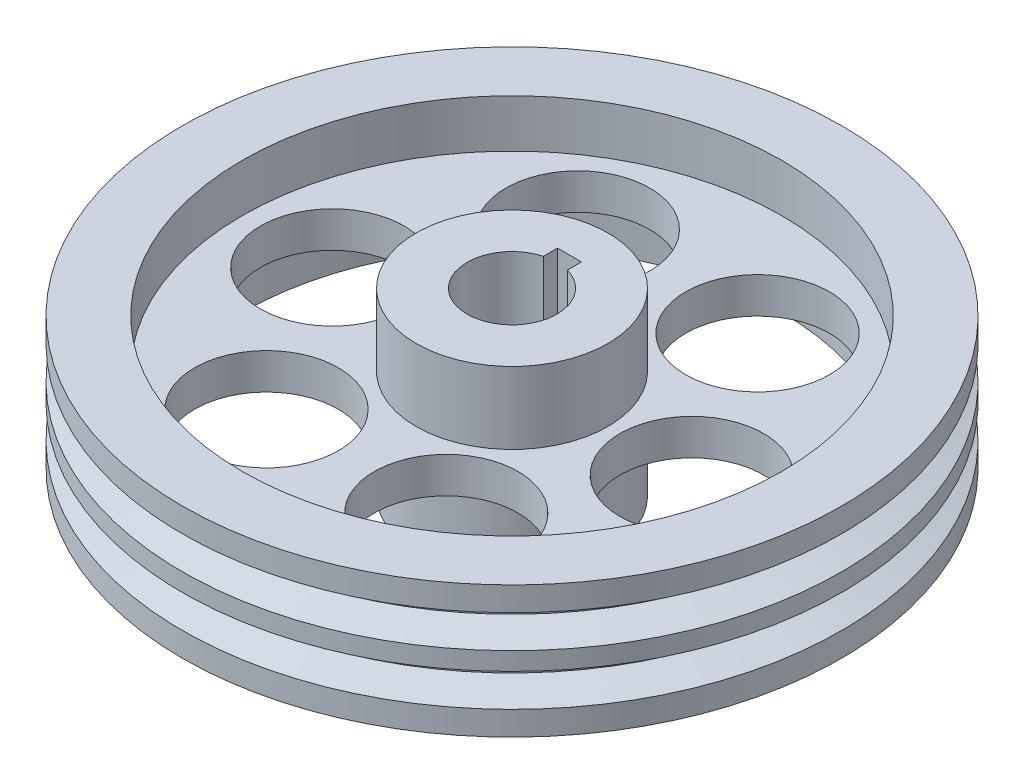
SolidWorks part; units mm, degrees
ref_plane "前视基准面" through (0, 0, 0) normal (0, 0, 1) x (1, 0, 0)
ref_plane "上视基准面" through (0, 0, 0) normal (0, 1, 0) x (1, 0, 0)
ref_plane "右视基准面" through (0, 0, 0) normal (1, 0, 0) x (0, 0, -1)
other "Configuration Table"
sketch "草图1" plane through (0, 0, 0) normal (0, 1, 0) x (1, 0, 0)
  line L0 (-2, 7.2284) -> (-2, 9.6)
  line L1 (-2, 9.6) -> (2, 9.6)
  line L2 (2, 9.6) -> (2, 7.2284)
  line L3 (0, 0) -> (0, 11.9601) construction
  arc A0 (-2, 7.2284) -> (0, 7.5) centre (0, 0) ccw
  circle A1 centre (0, 0) radius 16
  dimension "D1" = 15
  dimension "D2" = 32
  dimension "D3" = 9.6
  dimension "D4" = 4
extrude "凸台-拉伸1" add sketch "草图1" along normal mid plane 30
sketch "草图2" plane through (0, 0, 0) normal (0, 1, 0) x (1, 0, 0)
  circle A0 centre (0, 0) radius 30 construction
  circle A1 centre (-30, 0) radius 12
  circle A2 centre (-15, 25.9808) radius 12
  circle A3 centre (15, 25.9808) radius 12
  circle A4 centre (30, 0) radius 12
  circle A5 centre (15, -25.9808) radius 12
  circle A6 centre (-15, -25.9808) radius 12
  circle A7 centre (0, 0) radius 16
  circle A8 centre (0, 0) radius 45
  point P18 (0, 0)
  dimension "D1" = 60
  dimension "D2" = 24
  dimension "D4" = 90
  dimension "D3" = 6
extrude "凸台-拉伸3" add sketch "草图2" along normal mid plane 6 contours A8 | A1 | A2 | A6 | A5 | A4 | A3
sketch "草图3" plane through (0, 0, 0) normal (0, 1, 0) x (1, 0, 0)
  circle A0 centre (0, 0) radius 45
  circle A1 centre (0, 0) radius 55
  dimension "D1" = 110
extrude "凸台-拉伸4" add sketch "草图3" along normal mid plane 22
sketch "草图4" plane through (0, 0, 0) normal (0, 0, 1) x (1, 0, 0)
  line L0 (-78.6196, 0) -> (72.4445, 0) construction
  line L1 (-55, 1.5) -> (-50, 3.2216)
  line L2 (-55, 11) -> (-55, -11) construction
  line L3 (-50, 3.2216) -> (-50, 5.2635)
  line L4 (-50, 5.2635) -> (-55, 6.9852)
  line L5 (-55, -1.5) -> (-50, -3.2216)
  line L6 (-50, -3.2216) -> (-50, -5.2635)
  line L7 (-50, -5.2635) -> (-55, -6.9852)
  line L8 (-55, 6.9852) -> (-55, 1.5)
  line L9 (-55, -1.5) -> (-55, -6.9852)
  dimension "D1" = 38
  dimension "D2" = 2.0419
  dimension "D3" = 50
  dimension "D4" = 1.5
ref_axis "基准轴1" through (0, -16.5, 0) along (0, 1, 0)
revolve "切除-旋转1" cut sketch "草图4" angle 360 about axis through (0, -16.5, 0) along (0, 1, 0)
